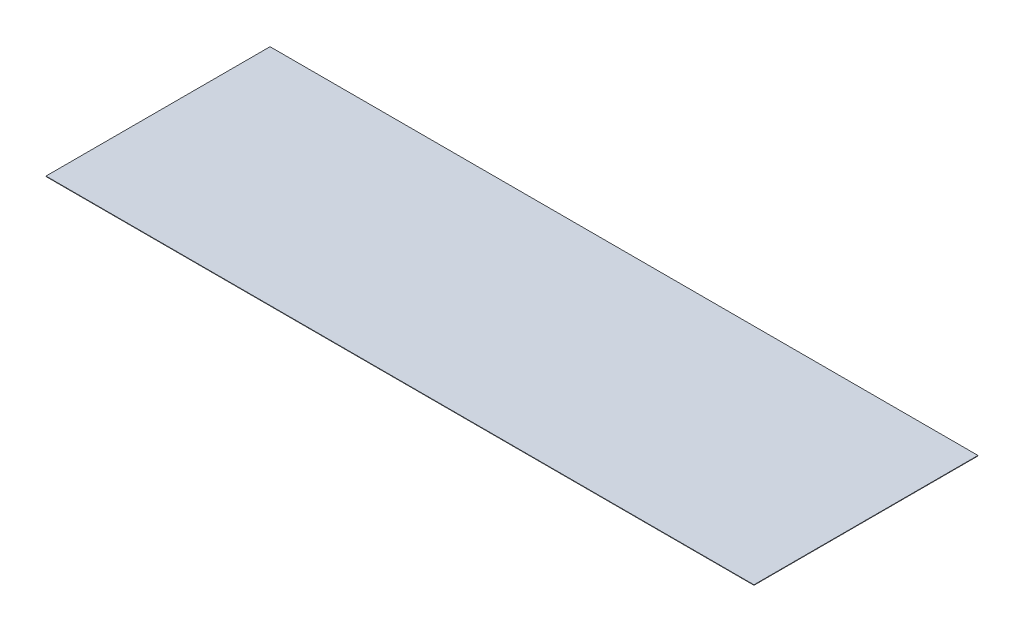
SolidWorks part; units mm, degrees
ref_plane "Front Plane" through (0, 0, 0) normal (0, 0, 1) x (1, 0, 0)
ref_plane "Top Plane" through (0, 0, 0) normal (0, 1, 0) x (1, 0, 0)
ref_plane "Right Plane" through (0, 0, 0) normal (1, 0, 0) x (0, 0, -1)
sketch "Sketch1" plane through (0, 0, 0) normal (0, 1, 0) x (1, 0, 0)
  line L1 (3950, -1250) -> (-3950, -1250)
  line L2 (3950, -1250) -> (3950, 1250)
  line L3 (3950, 1250) -> (-3950, 1250)
  line L4 (-3950, -1250) -> (-3950, 1250)
  line L5 (3950, -1250) -> (-3950, 1250) construction
  line L6 (3950, 1250) -> (-3950, -1250) construction
  point P0 (0, 0)
  dimension "D1" = 7900
  dimension "D2" = 2500
extrude "Boss-Extrude1" add sketch "Sketch1" along normal blind 5
